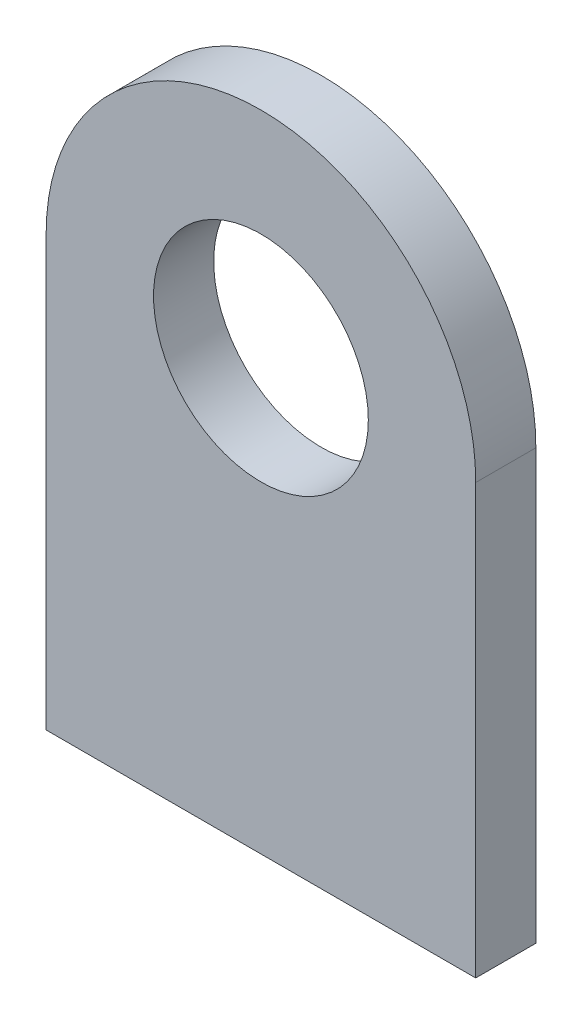
SolidWorks part; units mm, degrees
material "ASTM A36 Aço"
ref_plane "Plano frontal" through (0, 0, 0) normal (0, 0, 1) x (1, 0, 0)
ref_plane "Plano superior" through (0, 0, 0) normal (0, 1, 0) x (1, 0, 0)
ref_plane "Plano direito" through (0, 0, 0) normal (1, 0, 0) x (0, 0, -1)
sketch "Esboço1" plane through (0, 0, 0) normal (0, 0, 1) x (1, 0, 0)
  line L1 (-25, -50) -> (25, -50)
  line L2 (-25, -50) -> (-25, 0.0538)
  line L4 (25, -50) -> (25, -0.0538)
  line L5 (0, 0) -> (0, -50) construction
  line L6 (25, -0.0538) -> (25, -50)
  arc A0 (25, -0.0538) -> (-25, 0.0538) centre (0, 0) ccw
  circle A1 centre (0, 0) radius 12.5
  dimension "D3" = 25
  dimension "D1" = 50
  dimension "D2" = 50
extrude "Ressalto-extrusão1" add sketch "Esboço1" along normal blind 7
